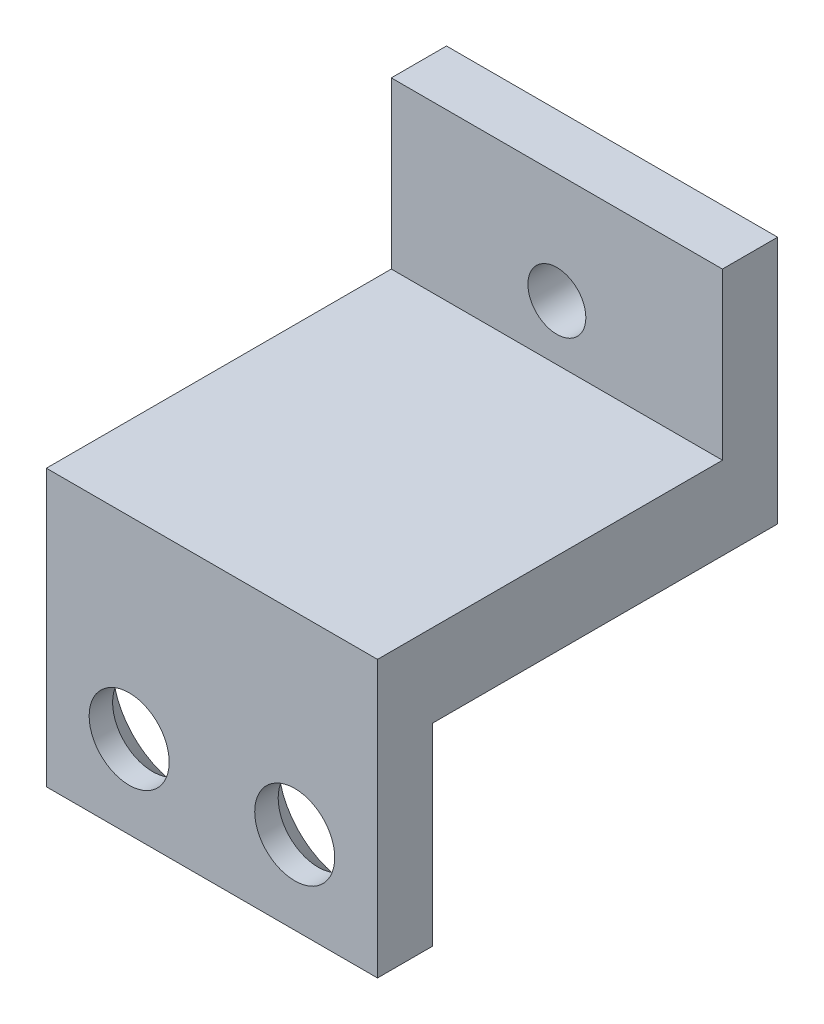
SolidWorks part; units mm, degrees
ref_plane "Front Plane" through (0, 0, 0) normal (0, 0, 1) x (1, 0, 0)
ref_plane "Top Plane" through (0, 0, 0) normal (0, 1, 0) x (1, 0, 0)
ref_plane "Right Plane" through (0, 0, 0) normal (1, 0, 0) x (0, 0, -1)
sketch "Sketch1" plane through (0, 0, 0) normal (0, 0, 1) x (1, 0, 0)
  line L1 (-26, 31) -> (-14, 31)
  line L2 (-26, 31) -> (-26, 40)
  line L3 (-26, 40) -> (-14, 40)
  line L4 (-14, 31) -> (-14, 40)
  circle A0 centre (-20, 36) radius 1.05
extrude "Link_Eye_Shelf" add sketch "Sketch1" along normal blind 2 from offset 14.5
sketch "Sketch2" plane through (0, 0, 0) normal (0, 0, 1) x (1, 0, 0)
  line L1 (-26, 31) -> (-14, 31)
  line L2 (-26, 31) -> (-26, 34)
  line L3 (-26, 34) -> (-14, 34)
  line L4 (-14, 31) -> (-14, 34)
extrude "Outboard_Web" add sketch "Sketch2" along normal blind 12.5 from offset 13.5
sketch "Sketch3" plane through (0, 0, 0) normal (0, 0, 1) x (1, 0, 0)
  line L1 (-26, 24) -> (-14, 24)
  line L2 (-26, 24) -> (-26, 34)
  line L3 (-26, 34) -> (-14, 34)
  line L4 (-14, 24) -> (-14, 34)
  circle A0 centre (-23, 27) radius 1.45
  circle A1 centre (-17, 27) radius 1.45
  dimension "D3" = 3
  dimension "D5" = 3
  dimension "D1" = 12
  dimension "D2" = 10
  dimension "D4" = 3
extrude "Intermediate_Plate_Foot" add sketch "Sketch3" along normal blind 2 from offset 2
chamfer "Chamfer1" distance 1.15 angle 45 2 edges at (-21.55, 27, -2) (-15.55, 27, -2)
